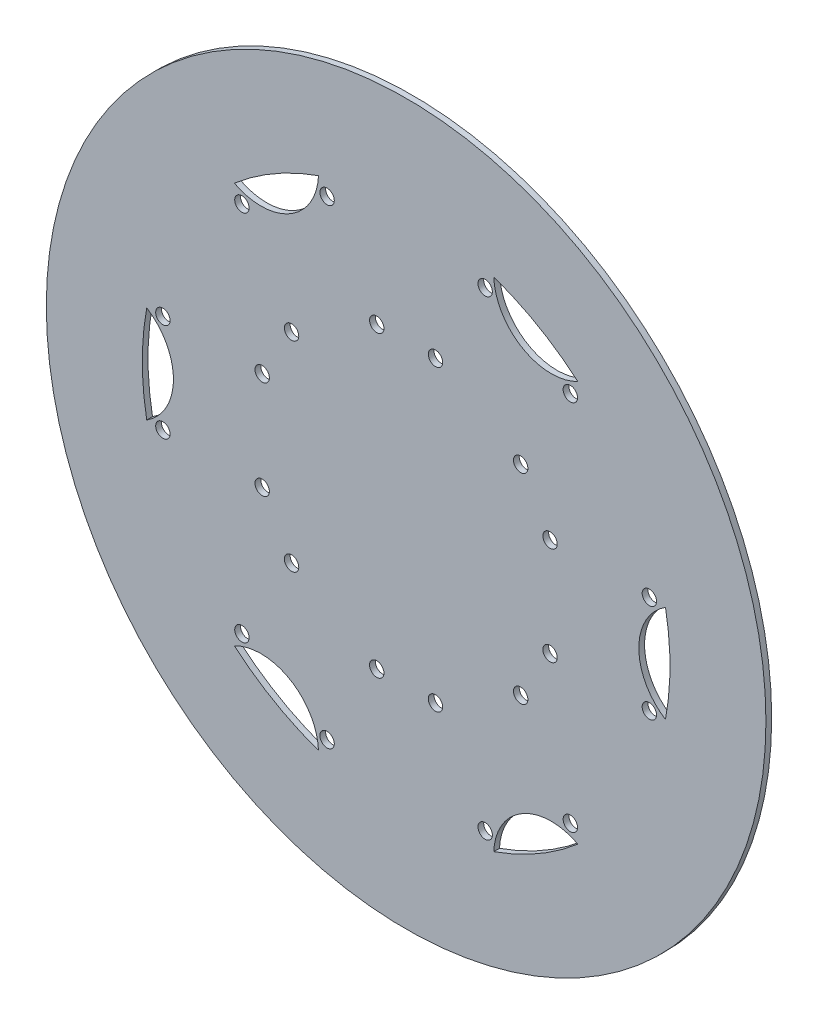
SolidWorks part; units mm, degrees
ref_plane "前视基准面" through (0, 0, 0) normal (0, 0, 1) x (1, 0, 0)
ref_plane "上视基准面" through (0, 0, 0) normal (0, 1, 0) x (1, 0, 0)
ref_plane "右视基准面" through (0, 0, 0) normal (1, 0, 0) x (0, 0, -1)
sketch "草图1" plane through (0, 0, 0) normal (0, 0, 1) x (1, 0, 0)
  circle A0 centre (0, 0) radius 75
  dimension "D1" = 150
extrude "凸台-拉伸1" add sketch "草图1" along normal blind 1.2
sketch "草图2" plane through (0, 0, 1.2) normal (0, 0, 1) x (1, 0, 0)
  line L0 (0, 55.1562) -> (0, -70.6268) construction
  line L1 (56.5822, 0) -> (-59.3265, 0) construction
  line L2 (-52.6571, -30.4016) -> (50.5035, 29.1582) construction
  line L3 (59.0862, -34.1134) -> (-52.7031, 30.4282) construction
  line L4 (0, 0) -> (-33.8927, 58.7038) construction
  line L5 (-6.1232, 31.1058) -> (-16.4732, 49.0325) construction
  line L6 (-16.4732, 49.0325) -> (-34.2268, 38.7825) construction
  line L7 (-34.2268, 38.7825) -> (-23.8768, 20.8558) construction
  line L8 (-23.8768, 20.8558) -> (-6.1232, 31.1058) construction
  circle A0 centre (-16.4732, 49.0325) radius 1.5
  circle A1 centre (-6.1232, 31.1058) radius 1.5
  circle A3 centre (-23.8768, 20.8558) radius 1.5
  circle A4 centre (-34.2268, 38.7825) radius 1.5
  arc A5 (-18.261, 51.88) -> (-35.7989, 41.7545) centre (-30.25, 52.3945) cw
  circle A6 centre (0, 0) radius 75 construction
  arc A7 (-18.261, 51.88) -> (-35.7989, 41.7545) centre (0, 0) ccw
  circle A8 centre (23.8768, 20.8558) radius 1.5
  circle A9 centre (6.1232, 31.1058) radius 1.5
  circle A10 centre (16.4732, 49.0325) radius 1.5
  circle A11 centre (34.2268, 38.7825) radius 1.5
  arc A12 (35.7989, 41.7545) -> (18.261, 51.88) centre (30.25, 52.3945) cw
  arc A13 (35.7989, 41.7545) -> (18.261, 51.88) centre (0, 0) ccw
  circle A14 centre (30, -10.25) radius 1.5
  circle A15 centre (30, 10.25) radius 1.5
  circle A16 centre (50.7, 10.25) radius 1.5
  circle A17 centre (50.7, -10.25) radius 1.5
  arc A18 (54.0599, -10.1255) -> (54.0599, 10.1255) centre (60.5, 0) cw
  arc A19 (54.0599, -10.1255) -> (54.0599, 10.1255) centre (0, 0) ccw
  circle A20 centre (6.1232, -31.1058) radius 1.5
  circle A21 centre (23.8768, -20.8558) radius 1.5
  circle A22 centre (34.2268, -38.7825) radius 1.5
  circle A23 centre (16.4732, -49.0325) radius 1.5
  arc A24 (18.261, -51.88) -> (35.7989, -41.7545) centre (30.25, -52.3945) cw
  arc A25 (18.261, -51.88) -> (35.7989, -41.7545) centre (0, 0) ccw
  circle A26 centre (-23.8768, -20.8558) radius 1.5
  circle A27 centre (-6.1232, -31.1058) radius 1.5
  circle A28 centre (-16.4732, -49.0325) radius 1.5
  circle A29 centre (-34.2268, -38.7825) radius 1.5
  arc A30 (-35.7989, -41.7545) -> (-18.261, -51.88) centre (-30.25, -52.3945) cw
  arc A31 (-35.7989, -41.7545) -> (-18.261, -51.88) centre (0, 0) ccw
  circle A32 centre (-30, 10.25) radius 1.5
  circle A33 centre (-30, -10.25) radius 1.5
  circle A34 centre (-50.7, -10.25) radius 1.5
  circle A35 centre (-50.7, 10.25) radius 1.5
  arc A36 (-54.0599, 10.1255) -> (-54.0599, -10.1255) centre (-60.5, 0) cw
  arc A37 (-54.0599, 10.1255) -> (-54.0599, -10.1255) centre (0, 0) ccw
  point P82 (0, 0)
  dimension "D8" = 3
  dimension "D9" = 3
  dimension "D10" = 3
  dimension "D11" = 3
  dimension "D12" = 12
  dimension "D1" = 60
  dimension "D2" = 30
  dimension "D3" = 30
  dimension "D4" = 20.7
  dimension "D5" = 20.5
  dimension "D6" = 10.25
  dimension "D7" = 30
  dimension "D13" = 30.5
  dimension "D14" = 6
extrude "切除-拉伸1" cut sketch "草图2" against normal through all
